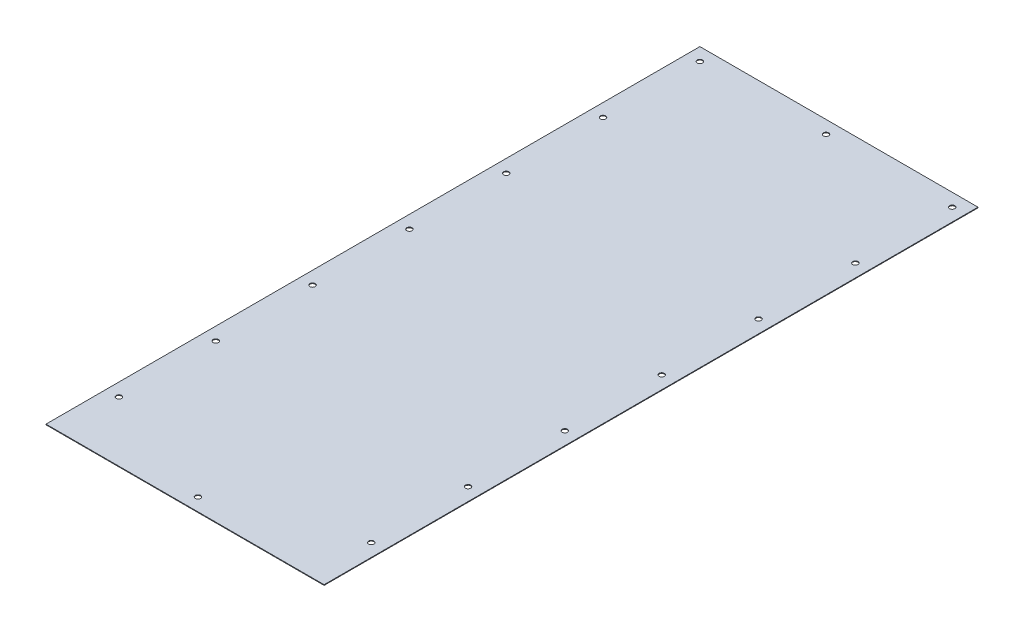
SolidWorks part; units mm, degrees
ref_plane "Front Plane" through (0, 0, 0) normal (0, 0, 1) x (1, 0, 0)
ref_plane "Top Plane" through (0, 0, 0) normal (0, 1, 0) x (1, 0, 0)
ref_plane "Right Plane" through (0, 0, 0) normal (1, 0, 0) x (0, 0, -1)
sketch "Sketch1" plane through (0, 0, 0) normal (0, 1, 0) x (1, 0, 0)
  line L1 (-215.425, 506.5) -> (215.425, 506.5)
  line L2 (-215.425, 506.5) -> (-215.425, -506.5)
  line L3 (-215.425, -506.5) -> (215.425, -506.5)
  line L4 (215.425, 506.5) -> (215.425, -506.5)
  line L5 (-215.425, 506.5) -> (215.425, -506.5) construction
  line L6 (-215.425, -506.5) -> (215.425, 506.5) construction
  line L7 (-195.425, -486.5) -> (195.425, -486.5) construction
  line L8 (-195.425, -486.5) -> (-195.425, 486.5) construction
  line L9 (-195.425, 486.5) -> (195.425, 486.5) construction
  line L10 (195.425, -486.5) -> (195.425, 486.5) construction
  line L11 (-195.425, -486.5) -> (195.425, 486.5) construction
  line L12 (-195.425, 486.5) -> (195.425, -486.5) construction
  circle A0 centre (-195.425, 486.5) radius 4.1
  circle A1 centre (195.425, 486.5) radius 4.1
  circle A2 centre (-195.425, 336.5) radius 4.1
  circle A3 centre (195.425, 336.5) radius 4.1
  circle A4 centre (-195.425, 186.5) radius 4.1
  circle A5 centre (195.425, 186.5) radius 4.1
  circle A6 centre (-195.425, 36.5) radius 4.1
  circle A7 centre (195.425, 36.5) radius 4.1
  circle A8 centre (-195.425, -113.5) radius 4.1
  circle A9 centre (195.425, -113.5) radius 4.1
  circle A10 centre (-195.425, -263.5) radius 4.1
  circle A11 centre (195.425, -263.5) radius 4.1
  circle A12 centre (-195.425, -413.5) radius 4.1
  circle A13 centre (195.425, -413.5) radius 4.1
  circle A26 centre (0, -486.5) radius 4.1
  circle A27 centre (0, 486.5) radius 4.1
  point P0 (0, 0)
  point P6 (0, 0)
  dimension "D5" = 8.2
  dimension "D7" = 8.2
  dimension "D8" = 8.2
  dimension "D1" = 1013
  dimension "D2" = 390.85
  dimension "D3" = 20
  dimension "D4" = 20
  dimension "D6" = 7
extrude "Boss-Extrude1" add sketch "Sketch1" along normal blind 1
